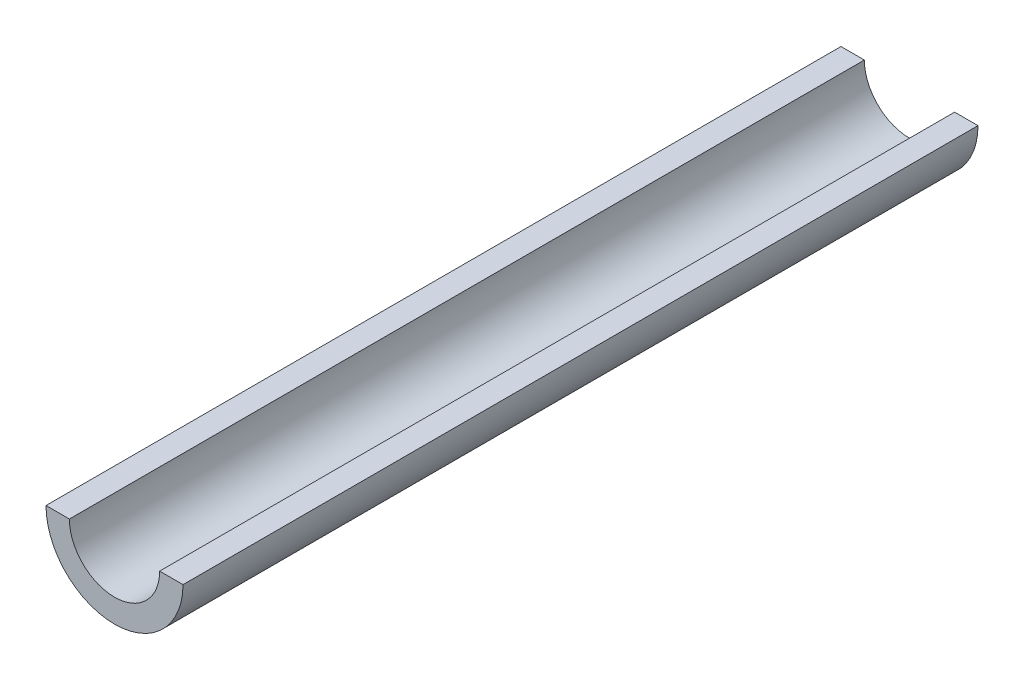
SolidWorks part; units mm, degrees
ref_plane "Front Plane" through (0, 0, 0) normal (0, 0, 1) x (1, 0, 0)
ref_plane "Top Plane" through (0, 0, 0) normal (0, 1, 0) x (1, 0, 0)
ref_plane "Right Plane" through (0, 0, 0) normal (1, 0, 0) x (0, 0, -1)
sketch "Sketch1" plane through (0, 0, 0) normal (0, 0, 1) x (1, 0, 0)
  line L0 (14.65, 0) -> (9.65, 0)
  line L1 (-9.65, 0) -> (-14.65, 0)
  arc A0 (-9.65, 0) -> (9.65, 0) centre (0, 0) ccw
  arc A1 (-14.65, 0) -> (14.65, 0) centre (0, 0) ccw
  circle A3 centre (0, 0) radius 9.65 construction
  circle A4 centre (0, 0) radius 14.65 construction
  point P1 (14.55, 0)
  point P5 (9.1327, 2.7921)
  point P8 (0, 0)
  dimension "D1" = 19.3
  dimension "D2" = 5
extrude "Boss-Extrude1" add sketch "Sketch1" along normal blind 170
